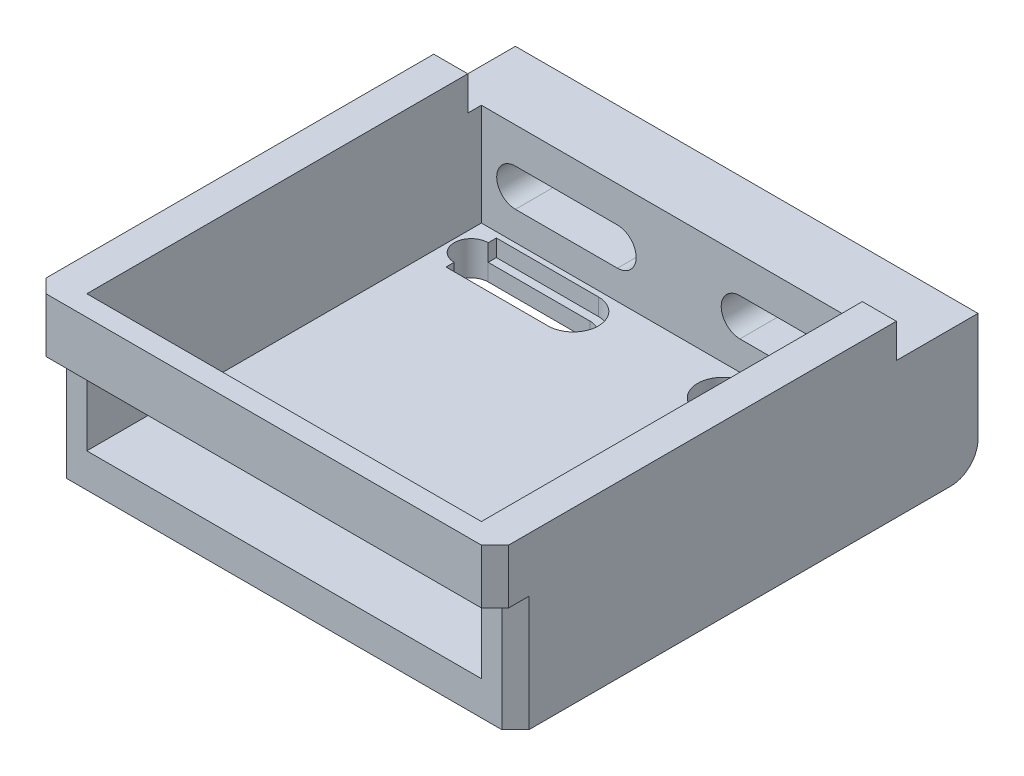
SolidWorks part; units mm, degrees
ref_plane "前视基准面" through (0, 0, 0) normal (0, 0, 1) x (1, 0, 0)
ref_plane "上视基准面" through (0, 0, 0) normal (0, 1, 0) x (1, 0, 0)
ref_plane "右视基准面" through (0, 0, 0) normal (1, 0, 0) x (0, 0, -1)
other "Configuration Table"
sketch "草图1" plane through (0, 0, 0) normal (1, 0, 0) x (0, 0, -1)
  line L0 (0, 0) -> (-68, 0)
  line L1 (-68, 0) -> (-68, 5)
  line L2 (-68, 5) -> (-10, 5)
  line L3 (-10, 5) -> (-10, 20)
  line L4 (-10, 20) -> (0, 20)
  line L5 (0, 20) -> (0, 0)
  dimension "D1" = 20
  dimension "D2" = 58
  dimension "D3" = 10
  dimension "D4" = 5
extrude "凸台-拉伸2" add sketch "草图1" along normal blind 68
sketch "草图2" plane through (0, 5, 0) normal (0, 1, 0) x (1, 0, 0)
  line L0 (5, -10) -> (5, -68)
  line L2 (63, -68) -> (63, -10)
  line L4 (0, -10) -> (0, -68)
  line L5 (0, -68) -> (68, -68)
  line L6 (68, -68) -> (68, -10)
  line L7 (68, -10) -> (0, -10)
  line L8 (0, -10) -> (0, -68)
  line L10 (68, -68) -> (68, -10)
  line L11 (68, -10) -> (63, -10)
  line L12 (63, -15) -> (5, -15) construction
  line L13 (5, -63) -> (63, -63) construction
  line L14 (0, -68) -> (68, -68) construction
  line L15 (5, -15) -> (5, -63) construction
  line L16 (63, -63) -> (63, -15) construction
  line L17 (68, -68) -> (0, -68) construction
  line L18 (68, -68) -> (63, -68)
  line L19 (68, -68) -> (63, -68)
  line L20 (5, -68) -> (0, -68)
  line L21 (5, -10) -> (0, -10)
  line L22 (68, -10) -> (0, -10) construction
  line M8 (0, -68) -> (68, -68)
  line M9 (68, -68) -> (68, -10)
  line M10 (68, -10) -> (0, -10)
  dimension "D1" = 0
  dimension "D2" = 5
extrude "凸台-拉伸3" add sketch "草图2" along normal blind 20 contours L2 M8 M9 M10 | L8 L20 L0 L21
sketch "草图3" plane through (0, 0, 0) normal (0, 0, -1) x (-1, 0, 0)
  line L0 (-58, 12) -> (-43, 12) construction
  line L1 (-58, 14.75) -> (-43, 14.75)
  line L2 (-58, 9.25) -> (-43, 9.25)
  line L3 (-25, 12) -> (-10, 12) construction
  line L4 (-25, 14.75) -> (-10, 14.75)
  line L5 (-25, 9.25) -> (-10, 9.25)
  line L6 (-68, 0) -> (0, 0) construction
  line L7 (-68, 0) -> (-68, 20) construction
  line L8 (0, 0) -> (0, 20) construction
  arc A0 (-58, 14.75) -> (-58, 9.25) centre (-58, 12) ccw
  arc A1 (-43, 9.25) -> (-43, 14.75) centre (-43, 12) ccw
  arc A2 (-25, 14.75) -> (-25, 9.25) centre (-25, 12) ccw
  arc A3 (-10, 9.25) -> (-10, 14.75) centre (-10, 12) ccw
  point P2 (-50.5, 12)
  point P7 (-17.5, 12)
  dimension "D1" = 12
  dimension "D2" = 5.5
  dimension "D3" = 5.5
  dimension "D4" = 15
  dimension "D5" = 15
  dimension "D6" = 10
  dimension "D7" = 10
extrude "切除-拉伸1" cut sketch "草图3" against normal blind 20
fillet "圆角1" radius 4 1 edges at (34, 0, 0)
sketch "草图4" plane through (0, 25, 0) normal (0, 1, 0) x (1, 0, 0)
  line L0 (68, -68) -> (68, -71)
  line L1 (68, -71) -> (0, -71)
  line L2 (0, -71) -> (0, -68)
  line L3 (0, -68) -> (68, -68)
  dimension "D1" = 3
extrude "凸台-拉伸4" add sketch "草图4" against normal blind 8
chamfer "倒角1" distance 2 angle 45 10 edges at (63, 22.5, 10) (68, 22.5, 10) (65.5, 25, 10) (5, 22.5, 10) (2.5, 25, 10) (0, 22.5, 10) (0, 8.5, 68) (68, 8.5, 68) (68, 21, 71) (0, 21, 71)
sketch "草图5" plane through (0, 0, 0) normal (0, -1, 0) x (1, 0, 0)
  line L0 (8, 14.5) -> (23, 14.5) construction
  line L1 (8, 17) -> (23, 17)
  line L2 (8, 12) -> (23, 12)
  line L3 (45, 14.5) -> (60, 14.5) construction
  line L4 (45, 17) -> (60, 17)
  line L5 (45, 12) -> (60, 12)
  line L6 (68, 66) -> (68, 4) construction
  line L7 (0, 66) -> (0, 4) construction
  line L8 (68, 0) -> (0, 0) construction
  arc A0 (8, 17) -> (8, 12) centre (8, 14.5) ccw
  arc A1 (23, 12) -> (23, 17) centre (23, 14.5) ccw
  arc A2 (45, 17) -> (45, 12) centre (45, 14.5) ccw
  arc A3 (60, 12) -> (60, 17) centre (60, 14.5) ccw
  point P2 (15.5, 14.5)
  point P7 (52.5, 14.5)
  dimension "D1" = 5
  dimension "D2" = 5
  dimension "D3" = 15
  dimension "D4" = 15
  dimension "D5" = 8
  dimension "D6" = 8
  dimension "D7" = 12
extrude "切除-拉伸3" cut sketch "草图5" against normal blind 8
sketch "草图7" plane through (0, 5, 0) normal (0, 1, 0) x (1, 0, 0)
  line L0 (23, -17) -> (8, -17) construction
  line L1 (23, -17) -> (8, -17)
  line L2 (60, -17) -> (45, -17) construction
  line L3 (45, -12) -> (60, -12) construction
  line L4 (63, -10) -> (5, -10)
  line L5 (5, -10) -> (5, -68)
  line L6 (5, -68) -> (63, -68)
  line L7 (63, -68) -> (63, -10)
  line L8 (63, -10) -> (5, -10)
  line L9 (5, -10) -> (5, -68)
  line L10 (5, -68) -> (63, -68)
  line L11 (63, -68) -> (63, -10)
  line L12 (60, -17) -> (45, -17)
  line L13 (45, -12) -> (60, -12)
  line L14 (8, -10.8) -> (8, -12)
  line L15 (8, -17) -> (8, -18.2)
  line L16 (8, -17) -> (23, -17)
  line L17 (8, -17) -> (23, -17)
  line L18 (60, -18.2) -> (45, -18.2)
  line L19 (8, -10.8) -> (23, -10.8)
  line L20 (8, -10.8) -> (23, -10.8)
  line L21 (45, -10.8) -> (60, -10.8)
  line L22 (23, -18.2) -> (8, -18.2)
  line L23 (60, -10.8) -> (60, -12)
  line L24 (60, -17) -> (60, -18.2)
  arc A0 (45, -12) -> (45, -17) centre (45, -14.5) ccw construction
  arc A1 (23, -17) -> (23, -12) centre (23, -14.5) ccw construction
  arc A2 (45, -12) -> (45, -17) centre (45, -14.5) ccw
  arc A3 (23, -17) -> (23, -12) centre (23, -14.5) ccw
  arc A4 (45, -10.8) -> (45, -18.2) centre (45, -14.5) ccw
  arc A5 (23, -18.2) -> (23, -10.8) centre (23, -14.5) ccw
  line M10 (23, -17) -> (8, -17)
  line M12 (8, -12) -> (23, -12)
  arc M13 (23, -12) -> (23, -17) centre (23, -14.5) cw
  line M14 (60, -17) -> (45, -17)
  arc M15 (45, -17) -> (45, -12) centre (45, -14.5) cw
  line M16 (45, -12) -> (60, -12)
  dimension "D1" = 0
  dimension "D2" = 5
  dimension "D3" = 1.2
  dimension "D4" = 1.2
  dimension "D5" = 1.2
extrude "切除-拉伸4" cut sketch "草图7" against normal blind 2.5 contours L22 A5 L20 L14 L15 M12 M13 M10 | L21 A4 L18 L24 L23 M14 M15 M16
